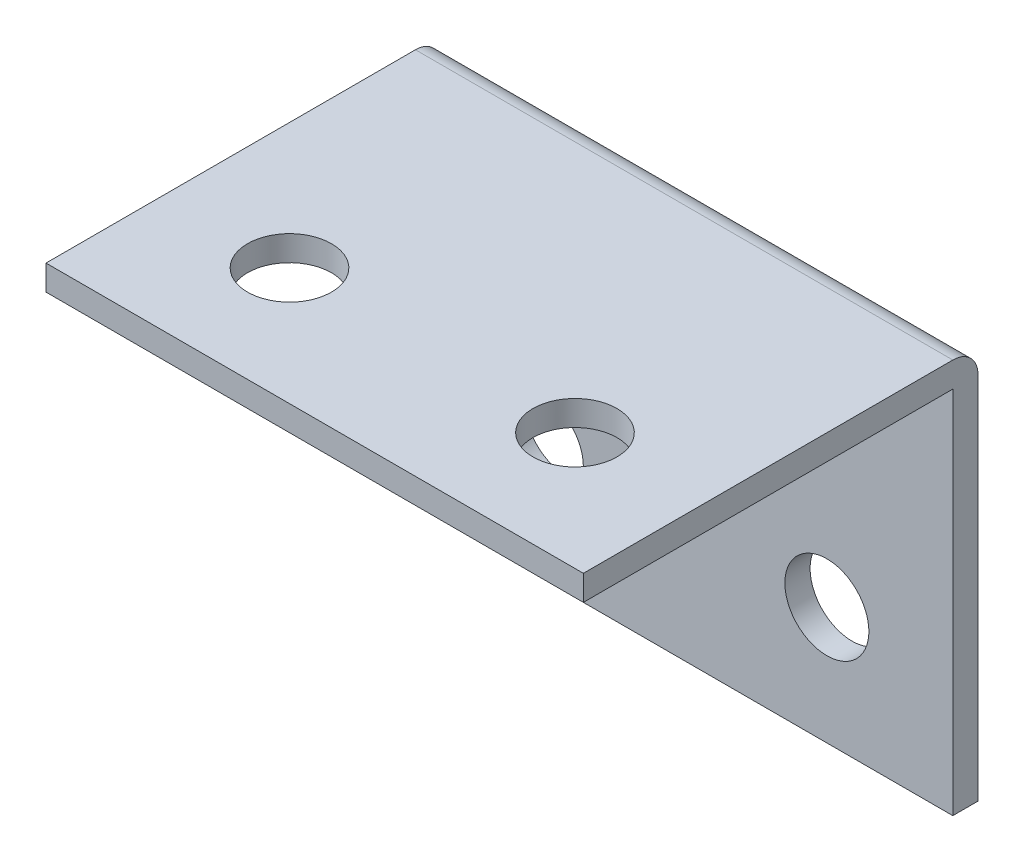
SolidWorks part; units mm, degrees
ref_plane "前视基准面" through (0, 0, 0) normal (0, 0, 1) x (1, 0, 0)
ref_plane "上视基准面" through (0, 0, 0) normal (0, 1, 0) x (1, 0, 0)
ref_plane "右视基准面" through (0, 0, 0) normal (1, 0, 0) x (0, 0, -1)
sketch "草图1" plane through (0, 0, 0) normal (0, 0, 1) x (1, 0, 0)
  line L1 (0, 0) -> (32, 0)
  line L2 (0, 0) -> (0, 23.5)
  line L3 (0, 23.5) -> (32, 23.5)
  line L4 (32, 0) -> (32, 23.5)
  dimension "D1" = 32
  dimension "D2" = 23.5
sketch "草图2" plane through (0, 0, 0) normal (0, 0, 1) x (1, 0, 0)
extrude "凸台-拉伸2" add sketch "草图1" along normal blind 23.5
shell "抽壳1" thickness 1.5
fillet "圆角2" radius 1.5 1 edges at (16, 23.5, 0)
sketch "草图3" plane through (0, 0, 1.5) normal (0, 0, 1) x (1, 0, 0)
  line L0 (16, 22) -> (16, 0) construction
  line L1 (32, 22) -> (0, 22) construction
  line L2 (0, 0) -> (32, 0) construction
  line L3 (-1.0524, 7) -> (33.1678, 7) construction
  circle A0 centre (7.5, 7) radius 2.5
  circle A1 centre (24.5, 7) radius 2.5
  dimension "D2" = 5
  dimension "D1" = 7
  dimension "D3" = 17
extrude "切除-拉伸2" cut sketch "草图3" against normal blind 23.5 contours A0 | A1
sketch "草图5" plane through (0, 22, 0) normal (0, -1, 0) x (1, 0, 0)
  line L0 (16, 23.5) -> (16, 2.1941) construction
  line L1 (32, 23.5) -> (0, 23.5) construction
  line L2 (0, 16.5) -> (32.6867, 16.5) construction
  line L3 (0, 23.5) -> (0, 1.5) construction
  circle A0 centre (7.5, 16.5) radius 2.5
  circle A1 centre (24.5, 16.5) radius 2.5
  dimension "D2" = 5
  dimension "D1" = 7
  dimension "D3" = 17
extrude "切除-拉伸3" cut sketch "草图5" against normal blind 23.5 contours A0 | A1
